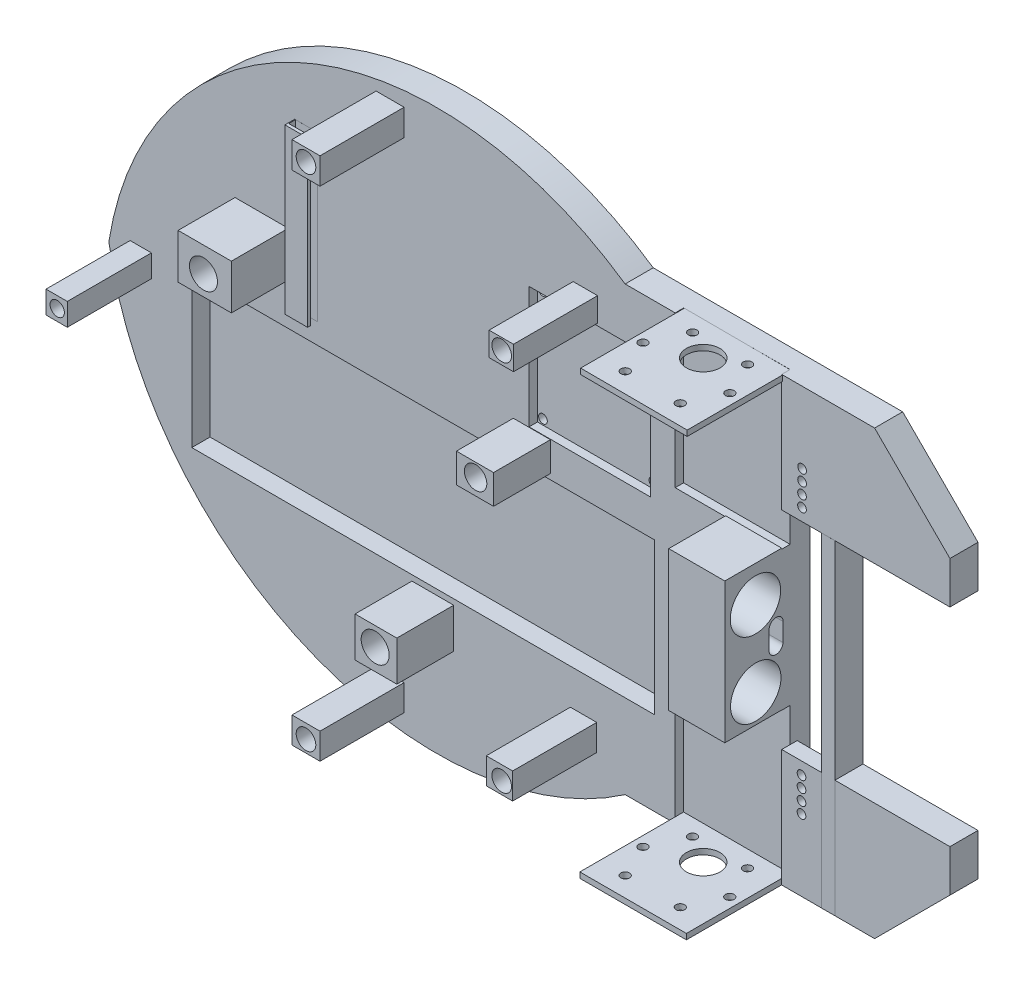
SolidWorks part; units mm, degrees
ref_plane "Front Plane" through (0, 0, 0) normal (0, 0, 1) x (1, 0, 0)
ref_plane "Top Plane" through (0, 0, 0) normal (0, 1, 0) x (1, 0, 0)
ref_plane "Right Plane" through (0, 0, 0) normal (1, 0, 0) x (0, 0, -1)
sketch "Sketch1" plane through (0, 0, 0) normal (0, 0, 1) x (1, 0, 0)
  line L1 (0, 0) -> (0, -37)
  line L2 (0, 37) -> (60, 37)
  line L3 (0, -37) -> (60, -37)
  line L4 (60, 37) -> (60, 52)
  line L5 (60, -37) -> (60, -52)
  line L6 (60, 52) -> (33.1299, 78.8701)
  line L7 (33.1299, 78.8701) -> (-55.8501, 78.8701)
  line L8 (60, -52) -> (33.1299, -78.8701)
  line L9 (33.1299, -78.8701) -> (-55.8501, -78.8701)
  line L10 (-55.8501, 78.8701) -> (-55.8501, 156.9436) construction
  line L11 (-55.8501, 156.9436) -> (-55.8501, -275.005) construction
  line L22 (0, 37) -> (0, 0)
  line L24 (-123.0632, 99.8019) -> (-270.1361, 99.8019) construction
  line L25 (-123.0632, 18.6512) -> (-123.0632, 134.1641) construction
  line L26 (-123.0632, -18.5763) -> (-123.0632, -116.9478) construction
  line L27 (-123.0632, -99.7887) -> (-269.8976, -99.7887) construction
  arc A7 (-239.9999, -0.1587) -> (-55.8501, 78.8701) centre (-123.0632, -18.5763) cw
  arc A8 (-55.8501, -78.8701) -> (-239.9999, -0.1587) centre (-123.0632, 18.6512) cw
  dimension "D11" = 199.5908
  dimension "D12" = 240
  dimension "D10" = 157.7401
  dimension "D1" = 37
  dimension "D2" = 37
  dimension "D3" = 60
  dimension "D4" = 15
  dimension "D5" = 15
  dimension "D6" = 135
  dimension "D7" = 38
  dimension "D8" = 38
  dimension "D9" = 135
  dimension "D15" = 88.98
  dimension "D16" = 88.98
extrude "Boss-Extrude1" add sketch "Sketch1" along normal blind 10 and the other way blind 0.01
sketch "Sketch3" plane through (0, 0, 10) normal (0, 0, 1) x (1, 0, 0)
  line L0 (33.1299, 78.8701) -> (-55.8501, 78.8701) construction
  line L1 (-38, 78.8701) -> (0, 78.8701)
  line L2 (-38, 78.8701) -> (-38, 24.8701)
  line L3 (-38, 24.8701) -> (0, 24.8701)
  line L4 (0, 78.8701) -> (0, 24.8701)
  point P6 (0, 0)
  point P7 (0, 0)
  point P8 (0, 0)
  point P9 (0, 0)
  point P10 (0, 0)
  dimension "D1" = 54
extrude "Cut-Extrude1" cut sketch "Sketch3" against normal blind 3 contours L2 L1 L4 L3
sketch "Sketch5" plane through (0, 0, 10) normal (0, 0, 1) x (1, 0, 0)
  line L0 (-55.8501, -78.8701) -> (33.1299, -78.8701) construction
  line L1 (-38, -24.8701) -> (0, -24.8701)
  line L2 (-38, -24.8701) -> (-38, -78.8701)
  line L3 (-38, -78.8701) -> (0, -78.8701)
  line L4 (0, -24.8701) -> (0, -78.8701)
  point P6 (0, 0)
  point P7 (0, 0)
  point P8 (0, 0)
  point P9 (0, 0)
  point P10 (0, 0)
  point P11 (0, 0)
  dimension "D1" = 54
extrude "Cut-Extrude3" cut sketch "Sketch5" against normal blind 3
sketch "Sketch7" plane through (0, 0, 10) normal (0, 0, 1) x (1, 0, 0)
  line L1 (-210.4131, 5.0562) -> (-45.4131, 5.0562)
  line L2 (-210.4131, 5.0562) -> (-210.4131, -48.9438)
  line L3 (-210.4131, -48.9438) -> (-45.4131, -48.9438)
  line L4 (-45.4131, 5.0562) -> (-45.4131, -48.9438)
  point P4 (0, 0)
  point P5 (0, 0)
  dimension "D1" = 54
  dimension "D2" = 165
extrude "Cut-Extrude4" cut sketch "Sketch7" against normal blind 6.5
sketch "Sketch8" plane through (0, 0, 10) normal (0, 0, 1) x (1, 0, 0)
  line L1 (-162.9927, 67.8133) -> (-84.7927, 67.8133)
  line L2 (-162.9927, 67.8133) -> (-162.9927, 10.3133)
  line L3 (-162.9927, 10.3133) -> (-84.7927, 10.3133)
  line L4 (-84.7927, 67.8133) -> (-84.7927, 10.3133)
  dimension "D1" = 78.2
  dimension "D2" = 57.5
extrude "Cut-Extrude5" [suppressed] cut sketch "Sketch8" against normal blind 3
sketch "Sketch9" plane through (0, 0, 10) normal (0, 0, 1) x (1, 0, 0)
  line L1 (-195, 36) -> (-176, 36)
  line L2 (-195, 36) -> (-195, 20)
  line L3 (-195, 20) -> (-176, 20)
  line L4 (-176, 36) -> (-176, 20)
  line L5 (-95.7317, 17.4542) -> (-82.493, 17.4542)
  line L6 (-95.7317, 17.4542) -> (-95.7317, 7.0108)
  line L7 (-95.7317, 7.0108) -> (-82.493, 7.0108)
  line L8 (-82.493, 17.4542) -> (-82.493, 7.0108)
  line L9 (-131.8867, -50.9252) -> (-116.9909, -50.9252)
  line L10 (-131.8867, -50.9252) -> (-131.8867, -65.1638)
  line L11 (-131.8867, -65.1638) -> (-116.9909, -65.1638)
  line L12 (-116.9909, -50.9252) -> (-116.9909, -65.1638)
  point P12 (0, 0)
  point P13 (0, 0)
  point P14 (0, 0)
  point P15 (0, 0)
  point P16 (0, 0)
  point P17 (0, 0)
  point P18 (0, 0)
  point P19 (0, 0)
  point P20 (0, 0)
extrude "Boss-Extrude2" add sketch "Sketch9" along normal blind 20.3
sketch "Sketch15" plane through (0, 0, 10) normal (0, 0, 1) x (1, 0, 0)
  line L0 (0, -24.8701) -> (0, 24.8701) construction
  line L1 (-20, 25.2016) -> (0, 25.2016)
  line L2 (-20, 25.2016) -> (-20, -24.7984)
  line L3 (-20, -24.7984) -> (0, -24.7984)
  line L4 (0, 25.2016) -> (0, -24.7984)
  dimension "D1" = 50
  dimension "D2" = 20
extrude "Boss-Extrude3" add sketch "Sketch15" along normal blind 20.3
sketch "Sketch16" plane through (0, 0, 10) normal (0, 0, 1) x (1, 0, 0)
  line L1 (-232.4208, 4) -> (-224.8235, 4)
  line L2 (-232.4208, 4) -> (-232.4208, -4)
  line L3 (-232.4208, -4) -> (-224.8235, -4)
  line L4 (-224.8235, 4) -> (-224.8235, -4)
  line L9 (-134.6881, 94.0493) -> (-144.6881, 94.0493)
  line L10 (-134.6881, 94.0493) -> (-134.6881, 84.6493)
  line L11 (-134.6881, 84.6493) -> (-144.6881, 84.6493)
  line L12 (-144.6881, 94.0493) -> (-144.6881, 84.6493)
  line L13 (-65.6779, 70.3488) -> (-74.3779, 70.3488)
  line L14 (-65.6779, 70.3488) -> (-65.6779, 61.8488)
  line L15 (-65.6779, 61.8488) -> (-74.3779, 61.8488)
  line L16 (-74.3779, 70.3488) -> (-74.3779, 61.8488)
  line L17 (-65.9779, -61.6233) -> (-75.3779, -61.6233)
  line L18 (-65.9779, -61.6233) -> (-65.9779, -70.9233)
  line L19 (-65.9779, -70.9233) -> (-75.3779, -70.9233)
  line L20 (-75.3779, -61.6233) -> (-75.3779, -70.9233)
  line L21 (-134.6881, -83.6815) -> (-144.6881, -83.6815)
  line L22 (-134.6881, -83.6815) -> (-134.6881, -92.9815)
  line L23 (-134.6881, -92.9815) -> (-144.6881, -92.9815)
  line L24 (-144.6881, -83.6815) -> (-144.6881, -92.9815)
extrude "Boss-Extrude4" add sketch "Sketch16" along normal blind 30
sketch "Sketch17" plane through (0, 0, 0) normal (0, 0, 1) x (1, 0, 0)
  circle A1 centre (-228.4208, 0) radius 2.55
  circle A2 centre (-139.6881, 89.6493) radius 3.5
  circle A3 centre (-69.8779, 66.3488) radius 3.5
  circle A4 centre (-69.8779, -66.6233) radius 3.5
  circle A5 centre (-139.6881, -88.6815) radius 3.5
extrude "Cut-Extrude17" cut sketch "Sketch17" along normal through all
sketch "Sketch18" plane through (0, 0, 10) normal (0, 0, 1) x (1, 0, 0)
  line L1 (-90.1245, 61) -> (-46.7245, 61)
  line L2 (-90.1245, 61) -> (-90.1245, 17.6)
  line L3 (-90.1245, 17.6) -> (-46.7245, 17.6)
  line L4 (-46.7245, 61) -> (-46.7245, 17.6)
  point P4 (0, 0)
  point P5 (0, 0)
  dimension "D1" = 43.4
  dimension "43.4" = 43.4
extrude "Cut-Extrude18" cut sketch "Sketch18" against normal blind 3
sketch "Sketch20" plane through (0, 0, 0) normal (0, 0, 1) x (1, 0, 0)
  circle A0 centre (-185.9471, 27.1121) radius 5
  circle A1 centre (-124.7094, -57.6129) radius 5
  circle A2 centre (-88.8879, 12.7504) radius 4
  point P6 (0, 0)
  point P7 (0, 0)
  point P8 (0, 0)
  point P9 (0, 0)
extrude "Cut-Extrude20" cut sketch "Sketch20" along normal through all
sketch "Sketch21" plane through (0, 0, 0) normal (1, 0, 0) x (0, 0, -1)
  line L0 (-3.8276, 29.0855) -> (-3.8276, -37.1575) construction
  line L1 (-6.4886, 28.3852) -> (-6.4886, -37.2976) construction
  line L2 (-5.0881, 28.1051) -> (-5.0881, -37.5777) construction
  line L3 (-11.99, 2.3019) -> (-12.0559, -4.1532) construction
  line L4 (-9.4916, 2.2764) -> (-9.5574, -4.1787)
  line L5 (-14.4885, 2.3274) -> (-14.5544, -4.1277)
  circle A0 centre (-19.3619, 12.3718) radius 9
  circle A1 centre (-19.2654, -14.6282) radius 9
  arc A2 (-9.4916, 2.2764) -> (-14.4885, 2.3274) centre (-11.99, 2.3019) ccw
  arc A3 (-14.5544, -4.1277) -> (-9.5574, -4.1787) centre (-12.0559, -4.1532) ccw
  point P12 (-12.023, -0.9256)
  dimension "D1" = 18
  dimension "D2" = 18
  dimension "D3" = 27
extrude "Cut-Extrude21" cut sketch "Sketch21" against normal up to surface (20 mm away) up to face at (-20, 5.1353, 18.12)
sketch "Sketch22" plane through (0, 0, 7) normal (0, 0, 1) x (1, 0, 0)
  circle A0 centre (-88.1686, 58.9795) radius 1.55
  circle A1 centre (-48.7686, 58.9795) radius 1.55
  circle A2 centre (-48.7686, 19.5795) radius 1.55
  circle A3 centre (-88.1686, 19.5795) radius 1.55
  point P3 (0, 0)
  dimension "D1" = 2
  dimension "D2" = 2
extrude "Cut-Extrude23" cut sketch "Sketch22" against normal through all
sketch "Sketch25" plane through (0, 0, 10) normal (0, 0, 1) x (1, 0, 0)
  line L1 (-173.6964, 70.8495) -> (-165.5964, 70.8495)
  line L2 (-173.6964, 70.8495) -> (-173.6964, 12.3495)
  line L3 (-173.6964, 12.3495) -> (-165.5964, 12.3495)
  line L4 (-165.5964, 70.8495) -> (-165.5964, 12.3495)
  point P4 (0, 0)
  dimension "D1" = 8.1
  dimension "D2" = 58.5
extrude "Boss-Extrude5" add sketch "Sketch25" along normal blind 3.5
sketch "Sketch26" plane through (0, 12.3495, 0) normal (0, -1, 0) x (1, 0, 0)
  line L0 (-172.679, 10.0037) -> (-152.674, 9.9893) construction
  line L1 (-152.674, 9.9893) -> (-152.6595, 14.6073) construction
  line L2 (-165.5928, 10.0085) -> (-173.4128, 10.0085)
  line L3 (-173.4128, 10.0085) -> (-173.4128, 12.4083)
  line L4 (-173.4128, 12.4083) -> (-165.5928, 12.4083)
  line L5 (-165.5928, 12.4083) -> (-165.5928, 10.0083)
  point P7 (0, 0)
  point P8 (0, 0)
  point P10 (0, 0)
  point P11 (0, 0)
  point P12 (0, 0)
  point P13 (0, 0)
  point P14 (0, 0)
  point P15 (0, 0)
  point P16 (0, 0)
  point P17 (0, 0)
  point P18 (0, 0)
  point P19 (0, 0)
  point P20 (0, 0)
  point P21 (0, 0)
  point P22 (0, 0)
  point P23 (0, 0)
  point P24 (0, 0)
  line M7 (-165.5964, 10) -> (-165.5964, 13.5)
extrude "Cut-Extrude24" cut sketch "Sketch26" against normal up to surface (58.5 mm away) contours L4 L3 L2 M7 up to face at (-169.6464, 70.8495, 11.75)
sketch "Sketch28" plane through (0, -78.8701, 0) normal (0, -1, 0) x (1, 0, 0)
  line L1 (14.2266, 10.0076) -> (18.9795, 10.0076)
  line L2 (14.2266, 10.0076) -> (14.2266, 0.0598)
  line L3 (14.2266, 0.0598) -> (18.9795, 0.0598)
  line L4 (18.9795, 10.0076) -> (18.9795, 0.0598)
extrude "Boss-Extrude6" add sketch "Sketch28" against normal up to surface (115.8701 mm away) up to face at (24, 37, 5.396)
sketch "Sketch30" plane through (0, 0, -0.01) normal (0, 0, -1) x (-1, 0, 0)
  line L0 (0.5881, -0.0011) -> (-26.6848, -0.0585) construction
  line L1 (0, -62) -> (-14.12, -62)
  line L2 (0, -62) -> (0, -37)
  line L3 (0, -37) -> (-14.12, -37)
  line L4 (-14.12, -62) -> (-14.12, -37)
  line L5 (-14.3807, 61.9354) -> (-14.2755, 36.9356)
  line L6 (-0.1557, 36.995) -> (-14.2755, 36.9356)
  line L7 (-0.2608, 61.9948) -> (-0.1557, 36.995)
  line L8 (-0.2608, 61.9948) -> (-14.3807, 61.9354)
  point P6 (0, 0)
  point P11 (0, 0)
  point P12 (0, 0)
  point P13 (0, 0)
  point P14 (0, 0)
  dimension "D1" = 25
  dimension "D2" = 14.12
extrude "Cut-Extrude25" cut sketch "Sketch30" against normal blind 4.5
sketch "Sketch33" plane through (0, 0, -0.01) normal (0, 0, -1) x (-1, 0, 0)
  line L0 (0, 0) -> (-115.8951, -0.2361) construction
  circle A0 centre (-7.06, -53.4) radius 1.55
  circle A1 centre (-7.06, -49.4) radius 1.55
  circle A2 centre (-7.06, -45.4) radius 1.55
  circle A3 centre (-7.06, -41.4) radius 1.55
  circle A4 centre (-7.2286, 41.3709) radius 1.55
  circle A5 centre (-7.2449, 45.3709) radius 1.55
  circle A6 centre (-7.2612, 49.3708) radius 1.55
  circle A7 centre (-7.2775, 53.3708) radius 1.55
  point P18 (0, 0)
  point P19 (0, 0)
  dimension "D1" = 4
extrude "Cut-Extrude26" cut sketch "Sketch33" against normal up to surface (10.01 mm away) up to face at (7.1133, -57.935, 10)
sketch "Sketch34" plane through (0, 0, 10) normal (0, 0, 1) x (1, 0, 0)
  line L0 (0, 0) -> (85.4359, -0.2266) construction
  line L1 (53.8089, -34.3247) -> (61.9289, -40.2214)
  line L2 (53.8089, -34.3247) -> (57.1772, -29.6864)
  line L3 (61.9289, -40.2214) -> (65.2973, -35.5831)
  line L4 (57.1772, -29.6864) -> (65.2973, -35.5831)
  line L5 (62.1414, 39.8924) -> (65.4851, 35.2362)
  line L6 (57.3338, 29.3826) -> (65.4851, 35.2362)
  line L7 (53.9902, 34.0388) -> (57.3338, 29.3826)
  line L8 (53.9902, 34.0388) -> (62.1414, 39.8924)
  point P8 (0, 0)
extrude "Cut-Extrude27" [suppressed] cut sketch "Sketch34" against normal through all
sketch "Sketch36" plane through (0, 0, 7) normal (0, 0, 1) x (1, 0, 0)
  line L0 (0, 0) -> (106.9048, -0.1896) construction
  line L1 (0.2795, 78.8146) -> (0.2724, 76.8146)
  line L2 (0, -78.8151) -> (-38, -78.8151)
  line L3 (0, -78.8151) -> (0, -76.8151)
  line L4 (0, -76.8151) -> (-38, -76.8151)
  line L5 (-38, -78.8151) -> (-38, -76.8151)
  line L6 (-37.7202, 78.9494) -> (-37.7273, 76.9494)
  line L7 (0.2724, 76.8146) -> (-37.7273, 76.9494)
  line L8 (0.2795, 78.8146) -> (-37.7202, 78.9494)
  dimension "D1" = 2
extrude "Boss-Extrude7" add sketch "Sketch36" along normal blind 37
sketch "Sketch39" plane through (0, -78.8151, 0) normal (0, -1, 0) x (1, 0, 0)
  line L1 (-46.4365, 25) -> (22.9075, 25) construction
  line L4 (31.9978, 332) -> (-461.8231, 332) construction
  circle A1 centre (-19, 19) radius 6
  circle A2 centre (-34.4996, 25.0106) radius 1.55
  circle A3 centre (-3.5639, 24.9888) radius 1.55
  circle A4 centre (-28.8192, 37.0106) radius 1.55
  circle A5 centre (-9.1774, 36.9888) radius 1.55
  circle A6 centre (-28.82, 13.0106) radius 1.55
  circle A7 centre (-9.2305, 12.9888) radius 1.55
  point P5 (0, 0)
  point P6 (0, 0)
  point P16 (-9.2305, 12.9888)
  point P18 (6.9989, 178.85)
  point P20 (0, 0)
  point P21 (0, 0)
  point P22 (0, 0)
  point P23 (0, 0)
  point P24 (0, 0)
  point P30 (0, 0)
  dimension "D1" = 12
  dimension "D5" = 12
  dimension "D6" = 12
  dimension "D7" = 12
  dimension "D8" = 12
  dimension "D2" = 19
extrude "Cut-Extrude28" cut sketch "Sketch39" against normal up to surface (2 mm away) up to face at (-19, -76.8151, 20.3333)
sketch "Sketch42" plane through (0.2795, 78.8146, 0) normal (0.0035, 1, 0) x (1, -0.0035, 0)
  circle A7 centre (-19.2797, -19) radius 6
  circle A9 centre (-29.0701, -13) radius 1.55
  circle A10 centre (-3.7784, -25) radius 1.55
  circle A11 centre (-9.4641, -13) radius 1.55
  circle A12 centre (-34.7723, -25) radius 1.55
  circle A13 centre (-29.0965, -37) radius 1.55
  circle A14 centre (-9.4734, -37) radius 1.55
  point P14 (-9.4734, -37)
  dimension "D1" = 12
  dimension "D5" = 6
  dimension "D6" = 6
  dimension "D7" = 6
  dimension "D8" = 6
  dimension "D9" = 18
  dimension "D10" = 18
  dimension "D2" = 19
extrude "Cut-Extrude29" cut sketch "Sketch42" against normal up to surface (2 mm away) up to face at (-12.485, 76.8599, 20.3333)
